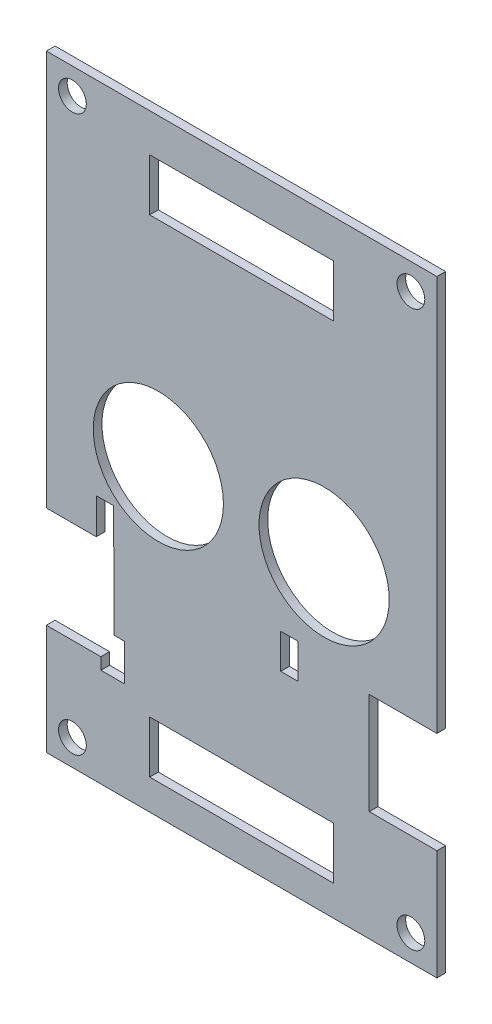
SolidWorks part; units mm, degrees
ref_plane "Front Plane" through (0, 0, 0) normal (0, 0, 1) x (1, 0, 0)
ref_plane "Top Plane" through (0, 0, 0) normal (0, 1, 0) x (1, 0, 0)
ref_plane "Right Plane" through (0, 0, 0) normal (1, 0, 0) x (0, 0, -1)
sketch "Sketch1" plane through (0, 0, 0) normal (0, 0, 1) x (1, 0, 0)
  line L0 (20.7342, -15.2835) -> (20.7342, -27.9835)
  line L1 (-24.2658, 42.0165) -> (20.7342, 42.0165)
  line L2 (-24.2658, 42.0165) -> (-24.2658, -3.5835)
  line L3 (-24.2658, -27.9835) -> (20.7342, -27.9835)
  line L4 (20.7342, 42.0165) -> (20.7342, -3.5835)
  line L5 (-24.2658, -3.5835) -> (-16.4658, -3.5835)
  line L7 (-24.2658, -15.2835) -> (-17.9858, -15.2835)
  line L8 (-16.4658, -3.5835) -> (-16.4658, -12.3835)
  line L9 (20.7342, -3.5835) -> (12.9342, -3.5835)
  line L10 (-24.2658, -15.2835) -> (-24.2658, -27.9835)
  line L11 (20.7342, -15.2835) -> (12.9342, -15.2835)
  line L12 (12.9342, -3.5835) -> (12.9342, -15.2835)
  line L13 (-15.2658, -12.3835) -> (-16.4658, -12.3835)
  line L14 (-15.2658, -12.3835) -> (-15.2658, -16.6335)
  line L15 (-15.2658, -16.6335) -> (-17.9858, -16.6335)
  line L16 (-17.9858, -15.2835) -> (-17.9858, -16.6335)
  circle A0 centre (-21.2658, 39.0165) radius 1.6
  circle A1 centre (17.7342, 39.0165) radius 1.6
  circle A2 centre (-21.2658, -24.9835) radius 1.6
  circle A3 centre (17.7342, -24.9835) radius 1.6
  dimension "D3" = 3
  dimension "D4" = 3
  dimension "D5" = 3
  dimension "D6" = 3
  dimension "D7" = 12.7
  dimension "D1" = 45
  dimension "D2" = 70
  dimension "D8" = 24.4
  dimension "D9" = 7.8
  dimension "D10" = 7.8
  dimension "D11" = 6.28
  dimension "D12" = 9
  dimension "D13" = 11.35
  dimension "D14" = 15.6
extrude "Boss-Extrude1" add sketch "Sketch1" along normal blind 1
sketch "Sketch2" plane through (0, 0, 1) normal (0, 0, 1) x (1, 0, 0)
  line L0 (-24.2658, -27.9835) -> (20.7342, -27.9835) construction
  line L1 (-24.2658, 42.0165) -> (-24.2658, -3.5835) construction
  circle A0 centre (-11.3658, 7.0165) radius 7.5
  circle A1 centre (7.7342, 7.0165) radius 7.5
  dimension "D1" = 35
  dimension "D2" = 12.9
  dimension "D3" = 35
  dimension "D4" = 32
sketch "Sketch4" plane through (0, 0, 1) normal (0, 0, 1) x (1, 0, 0)
  line L0 (-24.2658, 42.0165) -> (-24.2658, -3.5835) construction
  line L1 (-12.3658, -24.4835) -> (8.8342, -24.4835)
  line L2 (-12.3658, -24.4835) -> (-12.3658, -18.4835)
  line L3 (-12.3658, -18.4835) -> (8.8342, -18.4835)
  line L4 (8.8342, -24.4835) -> (8.8342, -18.4835)
  line L5 (-24.2658, -27.9835) -> (20.7342, -27.9835) construction
  line L7 (-12.3658, 31.6165) -> (8.8342, 31.6165)
  line L8 (-12.3658, 31.6165) -> (-12.3658, 37.6165)
  line L9 (-12.3658, 37.6165) -> (8.8342, 37.6165)
  line L10 (8.8342, 31.6165) -> (8.8342, 37.6165)
  dimension "D1" = 6
  dimension "D2" = 21.2
  dimension "D3" = 11.9
  dimension "D4" = 3.5
  dimension "D5" = 6
  dimension "D6" = 11.9
  dimension "D7" = 59.6
  dimension "D8" = 21.2
sketch "Sketch5" plane through (0, 0, 1) normal (0, 0, 1) x (1, 0, 0)
  line L0 (-24.2658, -27.9835) -> (20.7342, -27.9835) construction
  line L1 (-18.5158, 0.5165) -> (-16.5158, 0.5165)
  line L2 (-18.5158, 0.5165) -> (-18.5158, -3.9835)
  line L3 (-18.5158, -3.9835) -> (-16.5158, -3.9835)
  line L4 (-16.5158, 0.5165) -> (-16.5158, -3.9835)
  line L5 (-24.2658, 42.0165) -> (-24.2658, -3.5835) construction
  line L7 (2.7342, -2.3835) -> (4.7342, -2.3835)
  line L8 (2.7342, -2.3835) -> (2.7342, -6.3835)
  line L9 (2.7342, -6.3835) -> (4.7342, -6.3835)
  line L10 (4.7342, -2.3835) -> (4.7342, -6.3835)
  dimension "D1" = 4.5
  dimension "D2" = 2
  dimension "D3" = 24
  dimension "D4" = 5.75
  dimension "D5" = 2
  dimension "D6" = 4
  dimension "D7" = 21.6
  dimension "D8" = 27
extrude "Cut-Extrude1" cut sketch "Sketch5" against normal blind 4
extrude "Cut-Extrude2" cut sketch "Sketch4" against normal blind 4
extrude "Cut-Extrude3" cut sketch "Sketch2" against normal blind 4
